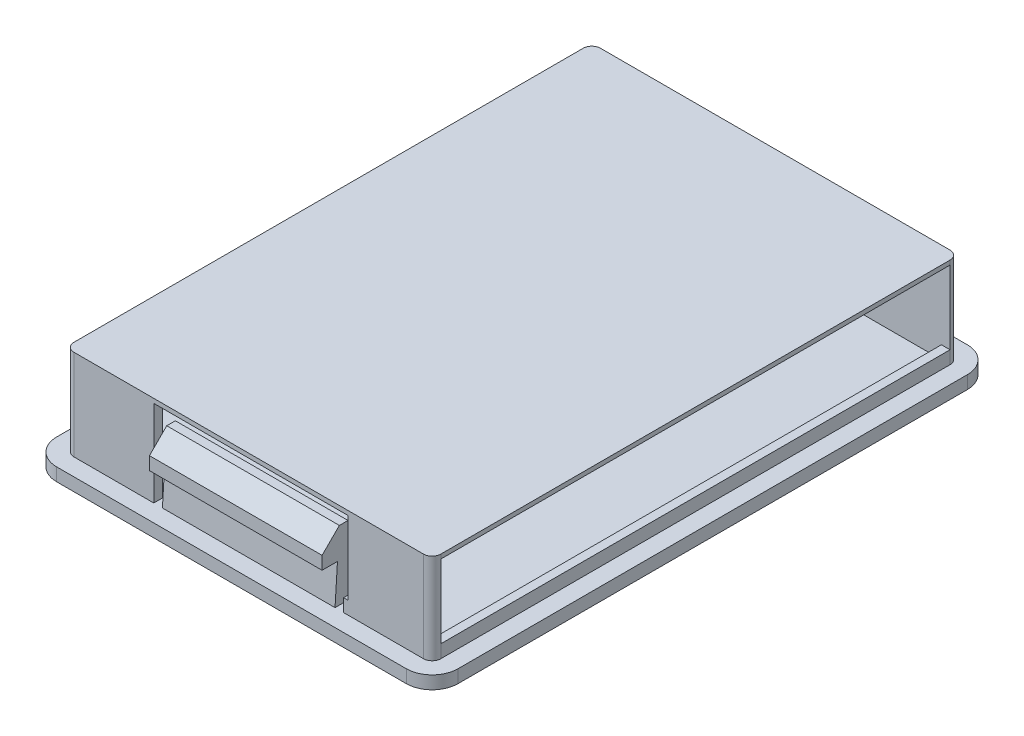
SolidWorks part; units mm, degrees
ref_plane "Front Plane" through (0, 0, 0) normal (0, 0, 1) x (1, 0, 0)
ref_plane "Top Plane" through (0, 0, 0) normal (0, 1, 0) x (1, 0, 0)
ref_plane "Right Plane" through (0, 0, 0) normal (1, 0, 0) x (0, 0, -1)
sketch "Sketch1" plane through (0, 0, 0) normal (0, 1, 0) x (1, 0, 0)
  line L1 (-23.25, -32.5) -> (23.25, -32.5)
  line L2 (-23.25, -32.5) -> (-23.25, 32.5)
  line L3 (-23.25, 32.5) -> (23.25, 32.5)
  line L4 (23.25, -32.5) -> (23.25, 32.5)
  line L5 (-23.25, -32.5) -> (23.25, 32.5) construction
  line L6 (-23.25, 32.5) -> (23.25, -32.5) construction
  point P0 (0, 0)
  dimension "D1" = 46.5
  dimension "D2" = 65
extrude "Boss-Extrude1" add sketch "Sketch1" along normal blind 1.5
fillet "Fillet1" radius 3 4 edges at (23.25, 0.75, 32.5) (-23.25, 0.75, 32.5) (-23.25, 0.75, -32.5) (23.25, 0.75, -32.5)
sketch "Sketch2" plane through (0, 1.5, 0) normal (0, 1, 0) x (1, 0, 0)
  line L0 (0, 0) -> (-50000, 0) construction
  line L1 (0, 0) -> (0, 50000) construction
  line L8 (20.25, 32.5) -> (-20.25, 32.5) construction
  line L9 (-10, 29) -> (10, 29)
  line L10 (-10, 29) -> (-10, 30.5)
  line L11 (-10, 30.5) -> (10, 30.5)
  line L12 (10, 29) -> (10, 30.5)
  line L13 (-10, 29) -> (10, 30.5) construction
  line L14 (-10, 30.5) -> (10, 29) construction
  point P5 (0, 29.75)
  dimension "D1" = 20
  dimension "D2" = 1.5
  dimension "D3" = 2
extrude "Boss-Extrude2" add sketch "Sketch2" along normal blind 8
sketch "Sketch5" plane through (-10, 0, 0) normal (-1, 0, 0) x (0, 0, 1)
  line L1 (-30.5, 9.5) -> (-29, 9.5) construction
  line L3 (-30.5, 9.5) -> (-30.5, 1.5)
  line L4 (-30.5, 1.5) -> (-30, 9.5)
  line L5 (-30, 9.5) -> (-30.5, 9.5)
  dimension "D1" = 0.5
extrude "Cut-Extrude1" cut sketch "Sketch5" against normal blind 24
sketch "Sketch6" plane through (-10, 0, 0) normal (-1, 0, 0) x (0, 0, 1)
  line L0 (-29, 9.5) -> (-30, 9.5)
  line L1 (-30, 9.5) -> (-32, 7.5)
  line L2 (-32, 7.5) -> (-32, 6)
  line L3 (-32, 6) -> (-29, 6)
  line L4 (-29, 9.5) -> (-29, 1.5) construction
  line L5 (-29, 6) -> (-29, 9.5)
  dimension "D1" = 3
  dimension "D2" = 3.5
  dimension "D3" = 1.5
extrude "Boss-Extrude5" add sketch "Sketch6" against normal up to surface (20 mm away) up to face at (10, 5.5, -29.625)
fillet "Fillet4" radius 0.5 1 edges at (0, 1.5, -29)
mirror "Mirror1" about plane through (0, 0, 0) normal (0, 0, 1) of "Cut-Extrude1", "Boss-Extrude2", "Boss-Extrude5", "Fillet4"
sketch "Sketch7" plane through (0, 1.5, 0) normal (0, 1, 0) x (1, 0, 0)
  line L0 (-11, 30.5) -> (-20.25, 30.5)
  line L1 (20.25, 30.5) -> (-20.25, 30.5) construction
  line L2 (-11, 29.5) -> (-20.25, 29.5)
  line L3 (20.25, 29.5) -> (-20.25, 29.5) construction
  line L4 (-20.25, 29.5) -> (-20.25, -29.5)
  line L5 (-20.25, -29.5) -> (-11, -29.5)
  line L6 (20.25, -29.5) -> (20.25, 29.5)
  line L7 (20.25, 29.5) -> (11, 29.5)
  line L8 (-20.25, -30.5) -> (20.25, -30.5)
  line L9 (21.25, -29.5) -> (21.25, 29.5)
  line L10 (20.25, 30.5) -> (-20.25, 30.5)
  line L11 (-21.25, 29.5) -> (-21.25, -29.5)
  line L12 (-20.25, -30.5) -> (-11, -30.5)
  line L13 (21.25, -29.5) -> (21.25, 29.5)
  line L14 (20.25, 30.5) -> (11, 30.5)
  line L15 (-21.25, 29.5) -> (-21.25, -29.5)
  line L16 (-11, 30.5) -> (-11, 29.5)
  line L17 (11, 30.5) -> (11, 29.5)
  line L18 (-10, 30.5) -> (-10, 28.5) construction
  line L19 (10, 28.5) -> (10, 30.5) construction
  line L20 (-11, -29.5) -> (-11, -30.5)
  line L21 (11, -29.5) -> (11, -30.5)
  line L22 (11, -29.5) -> (20.25, -29.5)
  line L23 (-20.25, -29.5) -> (20.25, -29.5) construction
  line L24 (11, -30.5) -> (20.25, -30.5)
  line L25 (-20.25, -30.5) -> (20.25, -30.5) construction
  arc A4 (-20.25, -29.5) -> (-20.25, -29.5) centre (-20.25, -29.5) ccw
  arc A5 (20.25, -29.5) -> (20.25, -29.5) centre (20.25, -29.5) ccw
  arc A6 (20.25, 29.5) -> (20.25, 29.5) centre (20.25, 29.5) ccw
  arc A7 (-20.25, 29.5) -> (-20.25, 29.5) centre (-20.25, 29.5) ccw
  arc A8 (20.25, -30.5) -> (21.25, -29.5) centre (20.25, -29.5) ccw
  arc A9 (21.25, 29.5) -> (20.25, 30.5) centre (20.25, 29.5) ccw
  arc A10 (-20.25, 30.5) -> (-21.25, 29.5) centre (-20.25, 29.5) ccw
  arc A11 (-21.25, -29.5) -> (-20.25, -30.5) centre (-20.25, -29.5) ccw
  arc A12 (20.25, -30.5) -> (21.25, -29.5) centre (20.25, -29.5) ccw
  arc A13 (21.25, 29.5) -> (20.25, 30.5) centre (20.25, 29.5) ccw
  arc A14 (-20.25, 30.5) -> (-21.25, 29.5) centre (-20.25, 29.5) ccw
  arc A15 (-21.25, -29.5) -> (-20.25, -30.5) centre (-20.25, -29.5) ccw
  dimension "D3" = 1
  dimension "D4" = 1
  dimension "D1" = 2
  dimension "D2" = 1
extrude "Boss-Extrude6" add sketch "Sketch7" along normal blind 1.5
ref_plane "Plane1" through (0, 11.5, 0) normal (0, 1, 0) x (1, 0, 0)
sketch "Sketch8" plane through (0, 11.5, 0) normal (0, 1, 0) x (1, 0, 0)
  line L0 (11, -30.5) -> (20.25, -30.5) construction
  line L3 (21.25, -29.5) -> (21.25, 29.5) construction
  line L4 (20.25, 30.5) -> (11, 30.5) construction
  line L6 (-20.25, -30.5) -> (-11, -30.5) construction
  line L7 (-21.25, 29.5) -> (-21.25, -29.5) construction
  line L9 (-11, 30.5) -> (-20.25, 30.5) construction
  line L11 (11, -30.5) -> (20.25, -30.5)
  line L14 (21.25, -29.5) -> (21.25, 29.5)
  line L15 (20.25, 30.5) -> (11, 30.5)
  line L17 (-20.25, -30.5) -> (-11, -30.5)
  line L18 (-21.25, 29.5) -> (-21.25, -29.5)
  line L20 (-11, 30.5) -> (-20.25, 30.5)
  line L21 (-11, 30.5) -> (11, 30.5)
  line L22 (-11, -30.5) -> (11, -30.5)
  arc A0 (20.25, -30.5) -> (21.25, -29.5) centre (20.25, -29.5) ccw construction
  arc A1 (21.25, 29.5) -> (20.25, 30.5) centre (20.25, 29.5) ccw construction
  arc A2 (-21.25, -29.5) -> (-20.25, -30.5) centre (-20.25, -29.5) ccw construction
  arc A3 (-20.25, 30.5) -> (-21.25, 29.5) centre (-20.25, 29.5) ccw construction
  arc A4 (20.25, -30.5) -> (21.25, -29.5) centre (20.25, -29.5) ccw
  arc A5 (21.25, 29.5) -> (20.25, 30.5) centre (20.25, 29.5) ccw
  arc A6 (-21.25, -29.5) -> (-20.25, -30.5) centre (-20.25, -29.5) ccw
  arc A7 (-20.25, 30.5) -> (-21.25, 29.5) centre (-20.25, 29.5) ccw
extrude "Boss-Extrude7" add sketch "Sketch8" along normal blind 0.5 separate body
sketch "Sketch9" plane through (0, 12, 0) normal (0, 1, 0) x (1, 0, 0)
  line L0 (20.25, 29.5) -> (11, 29.5)
  line L1 (-20.25, 29.5) -> (-20.25, -29.5)
  line L2 (-20.25, -29.5) -> (-11, -29.5)
  line L4 (20.25, 30.5) -> (-20.25, 30.5)
  line L5 (-21.25, 29.5) -> (-21.25, -29.5)
  line L6 (-20.25, -30.5) -> (20.25, -30.5)
  line L7 (21.25, -29.5) -> (21.25, 29.5)
  line L8 (20.25, 30.5) -> (11, 30.5)
  line L9 (-21.25, 29.5) -> (-21.25, -29.5)
  line L10 (-20.25, -30.5) -> (-11, -30.5)
  line L12 (-11, 30.5) -> (-11, 29.5)
  line L13 (-10, 30) -> (-10, 32) construction
  line L14 (11, 30.5) -> (11, 29.5)
  line L15 (10, 32) -> (10, 30) construction
  line L16 (-11, 30.5) -> (-20.25, 30.5)
  line L17 (20.25, 30.5) -> (-20.25, 30.5) construction
  line L18 (-11, 29.5) -> (-20.25, 29.5)
  line L19 (20.25, 29.5) -> (-20.25, 29.5) construction
  line L20 (20.25, 29.5) -> (21.25, 29.5)
  line L21 (-11, -30.5) -> (-11, -29.5)
  line L22 (20.25, -29.5) -> (20.25, 29.5) construction
  line L23 (21.25, -29.5) -> (21.25, 29.5) construction
  line L24 (-10, -30) -> (-10, -32) construction
  line L25 (20.25, -29.5) -> (21.25, -29.5)
  line L26 (11.5, -29.5) -> (11.5, -30.5)
  line L27 (10, -32) -> (10, -30) construction
  line L28 (11.5, -29.5) -> (20.25, -29.5)
  line L29 (-20.25, -29.5) -> (20.25, -29.5) construction
  line L30 (11.5, -30.5) -> (20.25, -30.5)
  line L31 (-20.25, -30.5) -> (20.25, -30.5) construction
  arc A0 (-20.25, 29.5) -> (-20.25, 29.5) centre (-20.25, 29.5) ccw
  arc A1 (-20.25, -29.5) -> (-20.25, -29.5) centre (-20.25, -29.5) ccw
  arc A2 (20.25, -29.5) -> (20.25, -29.5) centre (20.25, -29.5) ccw
  arc A3 (20.25, 29.5) -> (20.25, 29.5) centre (20.25, 29.5) ccw
  arc A4 (-20.25, 30.5) -> (-21.25, 29.5) centre (-20.25, 29.5) ccw
  arc A5 (-21.25, -29.5) -> (-20.25, -30.5) centre (-20.25, -29.5) ccw
  arc A6 (20.25, -30.5) -> (21.25, -29.5) centre (20.25, -29.5) ccw
  arc A7 (21.25, 29.5) -> (20.25, 30.5) centre (20.25, 29.5) ccw
  arc A8 (-20.25, 30.5) -> (-21.25, 29.5) centre (-20.25, 29.5) ccw
  arc A9 (-21.25, -29.5) -> (-20.25, -30.5) centre (-20.25, -29.5) ccw
  arc A10 (20.25, -30.5) -> (21.25, -29.5) centre (20.25, -29.5) ccw
  arc A11 (21.25, 29.5) -> (20.25, 30.5) centre (20.25, 29.5) ccw
  line M13 (20.25, 30.5) -> (-20.25, 30.5)
  line M17 (-20.25, -30.5) -> (20.25, -30.5)
  arc M18 (20.25, -30.5) -> (21.25, -29.5) centre (20.25, -29.5) ccw
  arc M20 (21.25, 29.5) -> (20.25, 30.5) centre (20.25, 29.5) ccw
  dimension "D3" = 1
  dimension "D4" = 1
  dimension "D5" = 1
  dimension "D6" = 1.5
  dimension "D1" = 0
  dimension "D2" = 1
extrude "Boss-Extrude8" add sketch "Sketch9" against normal up to surface (9 mm away) contours L0 L20 L14 M20 M13 | L28 L26 L25 M17 M18 | L1 A1 L2 L21 L10 A9 L9 A8 L16 L12 L18 A0
